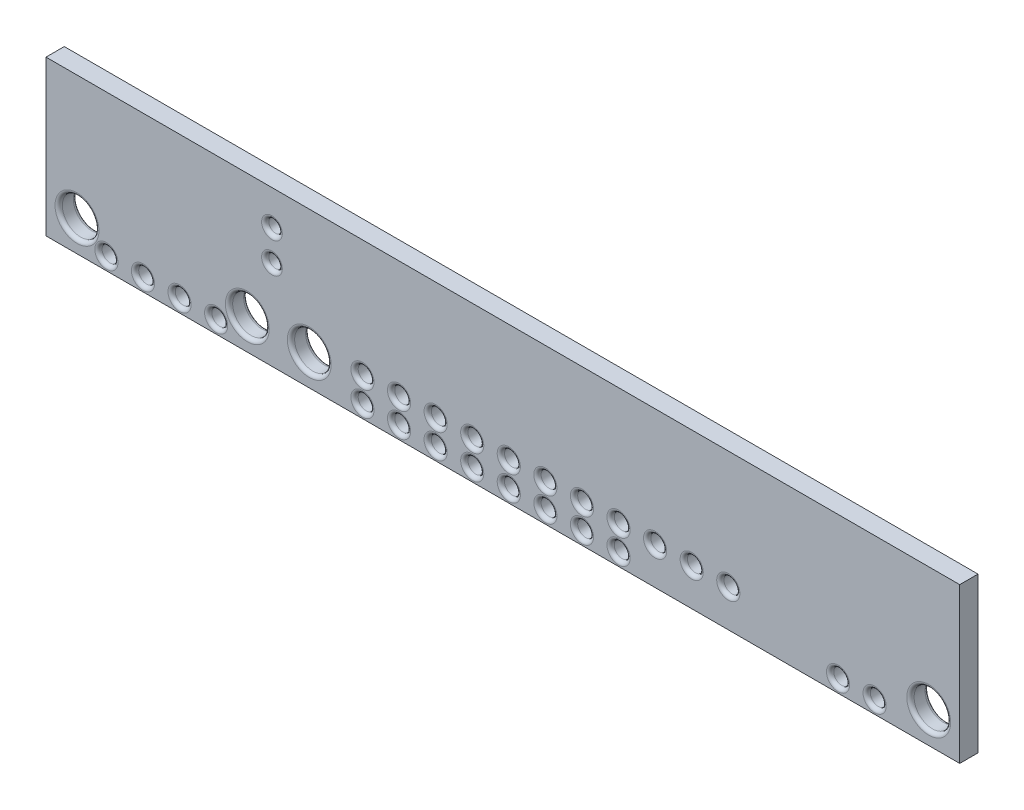
SolidWorks part; units mm, degrees
material "Placa de procesamiento, compleja"
ref_plane "Alzado" through (0, 0, 0) normal (0, 0, 1) x (1, 0, 0)
ref_plane "Planta" through (0, 0, 0) normal (0, 1, 0) x (1, 0, 0)
ref_plane "Vista lateral" through (0, 0, 0) normal (1, 0, 0) x (0, 0, -1)
sketch "Croquis3" plane through (0, 0, 0) normal (0, 0, 1) x (1, 0, 0)
  line L1 (-37.465, 6.35) -> (37.465, 6.35)
  line L2 (-37.465, 6.35) -> (-37.465, -6.35)
  line L3 (-37.465, -6.35) -> (37.465, -6.35)
  line L4 (37.465, 6.35) -> (37.465, -6.35)
  line L5 (-37.465, 6.35) -> (37.465, -6.35) construction
  line L6 (-37.465, -6.35) -> (37.465, 6.35) construction
  point P0 (0, 0)
  dimension "D1" = 74.93
  dimension "D2" = 12.7
extrude "Saliente-Extruir2" add sketch "Croquis3" along normal blind 1.5
sketch "Croquis4" plane through (0, 0, 1.5) normal (0, 0, 1) x (1, 0, 0)
  circle A0 centre (-34.925, -3.81) radius 1.5
  circle A1 centre (-20.955, -3.81) radius 1.5
  circle A2 centre (-15.875, -3.81) radius 1.5
  circle A3 centre (34.925, -3.81) radius 1.5
  circle A4 centre (-32.5126, -5.2934) radius 0.65
  circle A5 centre (-29.5126, -5.2934) radius 0.65
  circle A6 centre (-26.5126, -5.2934) radius 0.65
  circle A7 centre (-23.5126, -5.2934) radius 0.65
  circle A8 centre (-18.935, 1) radius 0.55
  circle A9 centre (-18.935, 3.5) radius 0.55
  circle A11 centre (-11.5126, -5.2934) radius 0.65
  circle A12 centre (-8.5126, -5.2934) radius 0.65
  circle A13 centre (-5.5126, -5.2934) radius 0.65
  circle A14 centre (-2.5126, -5.2934) radius 0.65
  circle A15 centre (0.4874, -5.2934) radius 0.65
  circle A16 centre (3.4874, -5.2934) radius 0.65
  circle A17 centre (6.4874, -5.2934) radius 0.65
  circle A18 centre (9.4874, -5.2934) radius 0.65
  circle A24 centre (27.4874, -5.2934) radius 0.65
  circle A25 centre (30.4874, -5.2934) radius 0.65
  circle A33 centre (-11.5126, -3.2934) radius 0.65
  circle A34 centre (-8.5126, -3.2934) radius 0.65
  circle A35 centre (-5.5126, -3.2934) radius 0.65
  circle A36 centre (-2.5126, -3.2934) radius 0.65
  circle A37 centre (0.4874, -3.2934) radius 0.65
  circle A38 centre (3.4874, -3.2934) radius 0.65
  circle A39 centre (6.4874, -3.2934) radius 0.65
  circle A40 centre (9.4874, -3.2934) radius 0.65
  circle A41 centre (12.4874, -3.2934) radius 0.65
  circle A42 centre (15.4874, -3.2934) radius 0.65
  circle A43 centre (18.4874, -3.2934) radius 0.65
  circle A50 centre (-20.5126, -3.2934) radius 0.65 [skipped]
  circle A51 centre (33.4874, -3.2934) radius 0.65 [skipped]
  circle A52 centre (33.4874, -5.2934) radius 0.65 [skipped]
  circle A53 centre (-32.5126, -3.2934) radius 0.65 [skipped]
  circle A54 centre (-29.5126, -3.2934) radius 0.65 [skipped]
  circle A55 centre (-26.5126, -3.2934) radius 0.65 [skipped]
  circle A56 centre (-23.5126, -3.2934) radius 0.65 [skipped]
  circle A57 centre (-20.5126, -5.2934) radius 0.65 [skipped]
  circle A58 centre (-17.5126, -5.2934) radius 0.65 [skipped]
  circle A59 centre (-17.5126, -3.2934) radius 0.65 [skipped]
  circle A60 centre (-14.5126, -5.2934) radius 0.65 [skipped]
  circle A61 centre (-14.5126, -3.2934) radius 0.65 [skipped]
  circle A62 centre (30.4874, -3.2934) radius 0.65 [skipped]
  circle A63 centre (27.4874, -3.2934) radius 0.65 [skipped]
  circle A64 centre (24.4874, -3.2934) radius 0.65 [skipped]
  circle A65 centre (24.4874, -5.2934) radius 0.65 [skipped]
  circle A66 centre (12.4874, -5.2934) radius 0.65 [skipped]
  circle A67 centre (15.4874, -5.2934) radius 0.65 [skipped]
  circle A68 centre (18.4874, -5.2934) radius 0.65 [skipped]
  circle A69 centre (21.4874, -5.2934) radius 0.65 [skipped]
  circle A70 centre (21.4874, -3.2934) radius 0.65 [skipped]
  dimension "D1" = 23
  dimension "D2" = 2
extrude "Cortar-Extruir1" cut sketch "Croquis4" against normal blind 3.175
fillet "Redondeo37" radius 0.3 1 edges at (-33.425, -3.81, 1.5)
fillet "Redondeo38" radius 0.3 1 edges at (-31.8626, -5.2934, 1.5)
fillet "Redondeo39" radius 0.3 1 edges at (-28.8626, -5.2934, 1.5)
fillet "Redondeo40" radius 0.3 1 edges at (-25.8626, -5.2934, 1.5)
fillet "Redondeo41" radius 0.3 1 edges at (-22.8626, -5.2934, 1.5)
fillet "Redondeo42" radius 0.3 1 edges at (-19.455, -3.81, 1.5)
fillet "Redondeo43" radius 0.3 1 edges at (-18.385, 1, 1.5)
fillet "Redondeo44" radius 0.3 1 edges at (-18.385, 3.5, 1.5)
fillet "Redondeo45" radius 0.3 1 edges at (-14.375, -3.81, 1.5)
fillet "Redondeo46" radius 0.3 1 edges at (-10.8626, -5.2934, 1.5)
fillet "Redondeo47" radius 0.3 1 edges at (-10.8626, -3.2934, 1.5)
fillet "Redondeo48" radius 0.3 1 edges at (-7.8626, -3.2934, 1.5)
fillet "Redondeo49" radius 0.3 1 edges at (-7.8626, -5.2934, 1.5)
fillet "Redondeo50" radius 0.3 1 edges at (-4.8626, -5.2934, 1.5)
fillet "Redondeo51" radius 0.3 1 edges at (-4.8626, -3.2934, 1.5)
fillet "Redondeo52" radius 0.3 1 edges at (-1.8626, -5.2934, 1.5)
fillet "Redondeo53" radius 0.3 1 edges at (-1.8626, -3.2934, 1.5)
fillet "Redondeo54" radius 0.3 1 edges at (1.1374, -3.2934, 1.5)
fillet "Redondeo55" radius 0.3 1 edges at (1.1374, -5.2934, 1.5)
fillet "Redondeo56" radius 0.3 1 edges at (4.1374, -5.2934, 1.5)
fillet "Redondeo57" radius 0.3 1 edges at (4.1374, -3.2934, 1.5)
fillet "Redondeo58" radius 0.3 1 edges at (7.1374, -3.2934, 1.5)
fillet "Redondeo59" radius 0.3 1 edges at (7.1374, -5.2934, 1.5)
fillet "Redondeo60" radius 0.3 1 edges at (10.1374, -5.2934, 1.5)
fillet "Redondeo61" radius 0.3 1 edges at (10.1374, -3.2934, 1.5)
fillet "Redondeo62" radius 0.3 1 edges at (13.1374, -3.2934, 1.5)
fillet "Redondeo63" radius 0.3 1 edges at (16.1374, -3.2934, 1.5)
fillet "Redondeo64" radius 0.3 1 edges at (19.1374, -3.2934, 1.5)
fillet "Redondeo65" radius 0.3 1 edges at (28.1374, -5.2934, 1.5)
fillet "Redondeo66" radius 0.3 1 edges at (31.1374, -5.2934, 1.5)
fillet "Redondeo67" radius 0.3 1 edges at (36.425, -3.81, 1.5)
fillet "Redondeo68" radius 0.3 1 edges at (36.425, -3.81, 0)
fillet "Redondeo69" radius 0.3 1 edges at (31.1374, -5.2934, 0)
fillet "Redondeo70" radius 0.3 1 edges at (28.1374, -5.2934, 0)
fillet "Redondeo71" radius 0.3 1 edges at (19.1374, -3.2934, 0)
fillet "Redondeo72" radius 0.3 1 edges at (16.1374, -3.2934, 0)
fillet "Redondeo73" radius 0.3 1 edges at (13.1374, -3.2934, 0)
fillet "Redondeo74" radius 0.3 1 edges at (10.1374, -3.2934, 0)
fillet "Redondeo75" radius 0.3 1 edges at (10.1374, -5.2934, 0)
fillet "Redondeo76" radius 0.3 1 edges at (7.1374, -5.2934, 0)
fillet "Redondeo77" radius 0.3 1 edges at (7.1374, -3.2934, 0)
fillet "Redondeo78" radius 0.3 1 edges at (4.1374, -3.2934, 0)
fillet "Redondeo79" radius 0.3 1 edges at (4.1374, -5.2934, 0)
fillet "Redondeo80" radius 0.3 1 edges at (1.1374, -5.2934, 0)
fillet "Redondeo81" radius 0.3 1 edges at (1.1374, -3.2934, 0)
fillet "Redondeo82" radius 0.3 1 edges at (-1.8626, -3.2934, 0)
fillet "Redondeo83" radius 0.3 1 edges at (-1.8626, -5.2934, 0)
fillet "Redondeo84" radius 0.3 1 edges at (-4.8626, -5.2934, 0)
fillet "Redondeo85" radius 0.3 1 edges at (-4.8626, -3.2934, 0)
fillet "Redondeo86" radius 0.3 1 edges at (-7.8626, -3.2934, 0)
fillet "Redondeo87" radius 0.3 1 edges at (-7.8626, -5.2934, 0)
fillet "Redondeo88" radius 0.3 1 edges at (-10.8626, -5.2934, 0)
fillet "Redondeo89" radius 0.3 1 edges at (-10.8626, -3.2934, 0)
fillet "Redondeo90" radius 0.3 1 edges at (-14.375, -3.81, 0)
fillet "Redondeo91" radius 0.3 1 edges at (-18.385, 1, 0)
fillet "Redondeo92" radius 0.3 1 edges at (-18.385, 3.5, 0)
fillet "Redondeo93" radius 0.3 1 edges at (-19.455, -3.81, 0)
fillet "Redondeo94" radius 0.3 1 edges at (-22.8626, -5.2934, 0)
fillet "Redondeo95" radius 0.3 1 edges at (-25.8626, -5.2934, 0)
fillet "Redondeo96" radius 0.3 1 edges at (-28.8626, -5.2934, 0)
fillet "Redondeo97" radius 0.3 1 edges at (-31.8626, -5.2934, 0)
fillet "Redondeo98" radius 0.3 1 edges at (-33.425, -3.81, 0)
